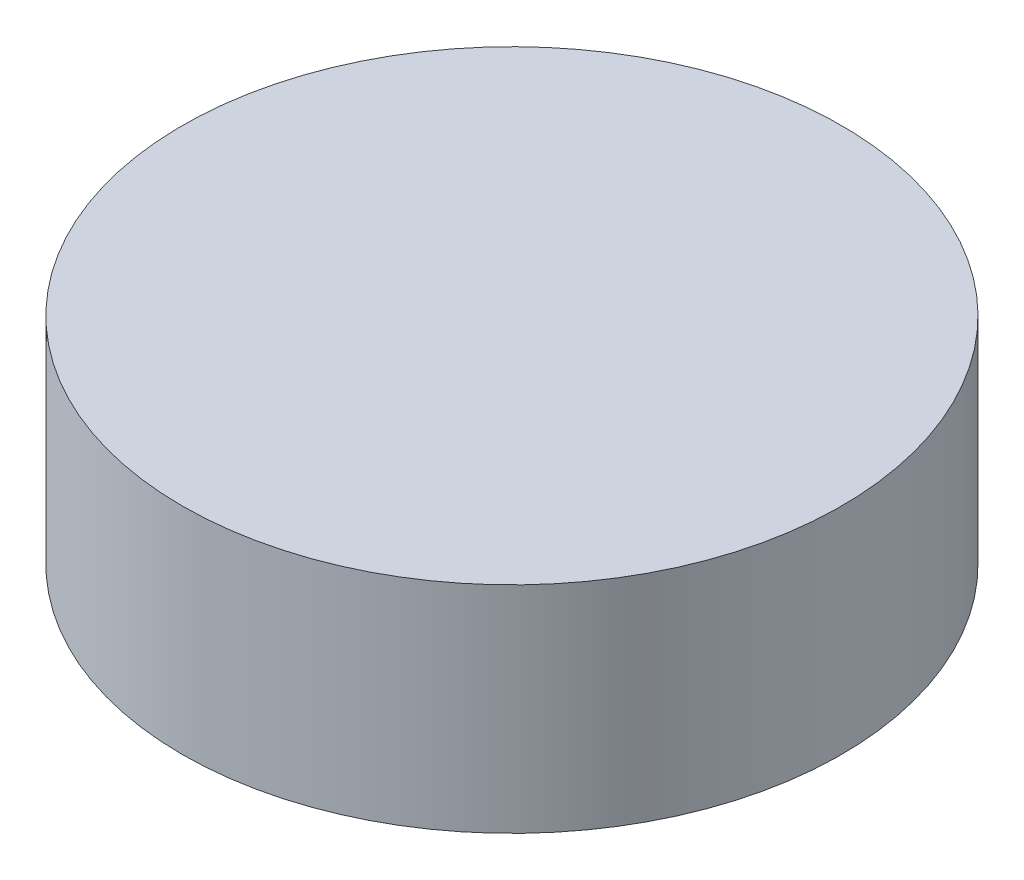
SolidWorks part; units mm, degrees
ref_plane "前视基准面" through (0, 0, 0) normal (0, 0, 1) x (1, 0, 0)
ref_plane "上视基准面" through (0, 0, 0) normal (0, 1, 0) x (1, 0, 0)
ref_plane "右视基准面" through (0, 0, 0) normal (1, 0, 0) x (0, 0, -1)
other "Configuration Table"
sketch "草图1" plane through (0, 0, 0) normal (0, 1, 0) x (1, 0, 0)
  circle A0 centre (0, 0) radius 2.45
  dimension "D1" = 4.9
extrude "凸台-拉伸1" add sketch "草图1" along normal blind 1.6
